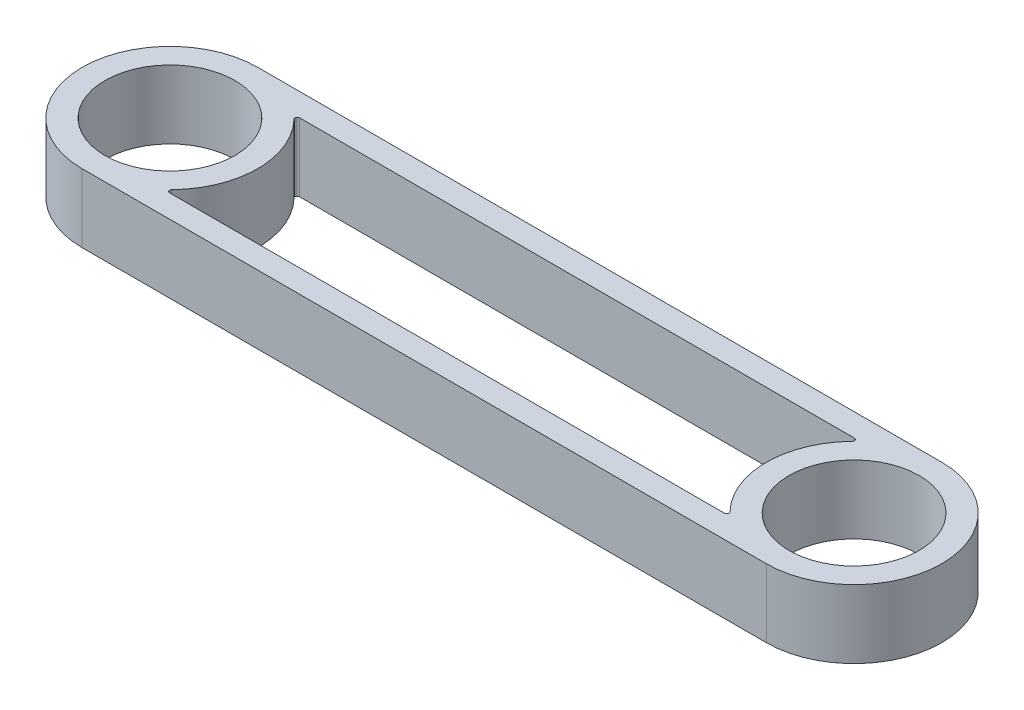
SolidWorks part; units mm, degrees
ref_plane "前视基准面" through (0, 0, 0) normal (0, 0, 1) x (1, 0, 0)
ref_plane "上视基准面" through (0, 0, 0) normal (0, 1, 0) x (1, 0, 0)
ref_plane "右视基准面" through (0, 0, 0) normal (1, 0, 0) x (0, 0, -1)
sketch "草图1" plane through (0, 0, 0) normal (0, 1, 0) x (1, 0, 0)
  line L0 (28.3549, -28.5) -> (271.6451, -28.5)
  line L1 (-46.3283, 0) -> (52.0613, 0) construction
  line L2 (0, 30.0611) -> (0, -44.0924) construction
  line L3 (0, -38.5) -> (300, -38.5)
  line L4 (150, 45.2308) -> (150, -61.2332) construction
  line L5 (0, 38.5) -> (300, 38.5)
  line L6 (28.3549, 28.5) -> (271.6451, 28.5)
  circle A0 centre (0, 0) radius 28.5
  arc A1 (27.637, -26.8038) -> (27.637, 26.8038) centre (0, 0) ccw
  arc A2 (0, 38.5) -> (0, -38.5) centre (0, 0) ccw
  arc A3 (28.3549, 28.5) -> (27.637, 26.8038) centre (28.3549, 27.5) ccw
  arc A4 (27.637, -26.8038) -> (28.3549, -28.5) centre (28.3549, -27.5) ccw
  arc A5 (300, 38.5) -> (300, -38.5) centre (300, 0) cw
  circle A6 centre (300, 0) radius 28.5
  arc A7 (272.363, -26.8038) -> (272.363, 26.8038) centre (300, 0) cw
  arc A8 (272.363, -26.8038) -> (271.6451, -28.5) centre (271.6451, -27.5) cw
  arc A9 (271.6451, 28.5) -> (272.363, 26.8038) centre (271.6451, 27.5) cw
  point P25 (150, 38.5)
  point P26 (150, 28.5)
  point P28 (150, -38.5)
  point P29 (150, -28.5)
  dimension "D1" = 57
  dimension "D2" = 10
  dimension "D4" = 1
  dimension "D3" = 150
extrude "凸台-拉伸1" add sketch "草图1" along normal blind 30
